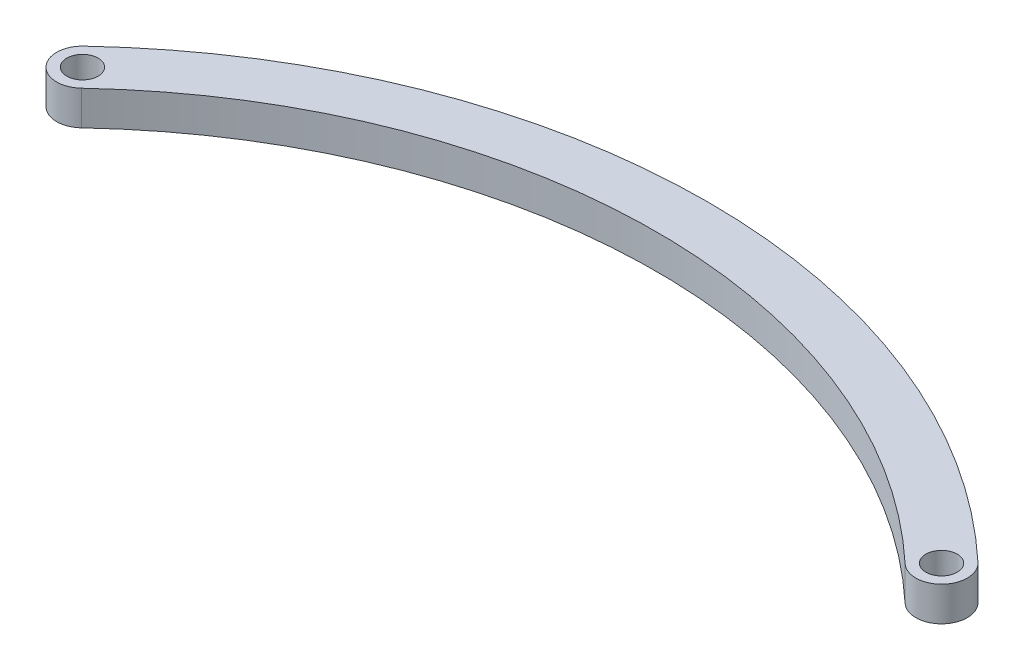
SolidWorks part; units mm, degrees
ref_plane "Front Plane" through (0, 0, 0) normal (0, 0, 1) x (1, 0, 0)
ref_plane "Top Plane" through (0, 0, 0) normal (0, 1, 0) x (1, 0, 0)
ref_plane "Right Plane" through (0, 0, 0) normal (1, 0, 0) x (0, 0, -1)
sketch "Esquisse1" plane through (0, 0, 0) normal (0, 1, 0) x (1, 0, 0)
  line L0 (-50, 0) -> (0, 0) construction
  line L1 (0, 0) -> (50, 0) construction
  circle A0 centre (-50, 0) radius 1.825
  circle A1 centre (50, 0) radius 1.825
  circle A2 centre (-50, 0) radius 3
  circle A3 centre (50, 0) radius 3
  circle A4 centre (0, -53.1883) radius 70
  circle A5 centre (0, -53.1883) radius 76
  dimension "D2" = 3.65
  dimension "D3" = 6
  dimension "D4" = 140
  dimension "D5" = 152
  dimension "D1" = 50
extrude "Boss.-Extru.1" add sketch "Esquisse1" along normal blind 4 contours A3 A5 A2 A4 | A2 A0 | A3 A1
